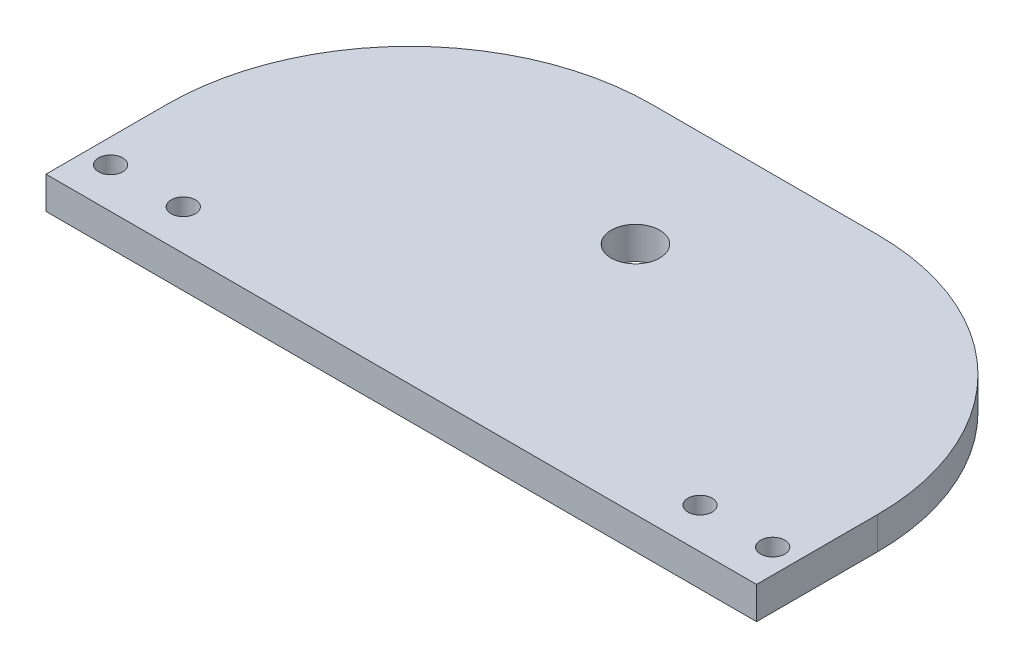
SolidWorks part; units mm, degrees
material "环氧树脂,未充填"
ref_plane "前视基准面" through (0, 0, 0) normal (0, 0, 1) x (1, 0, 0)
ref_plane "上视基准面" through (0, 0, 0) normal (0, 1, 0) x (1, 0, 0)
ref_plane "右视基准面" through (0, 0, 0) normal (1, 0, 0) x (0, 0, -1)
sketch "草图1" plane through (0, 0, 0) normal (0, 1, 0) x (1, 0, 0)
  line L1 (-44, 22.5) -> (44, 22.5)
  line L2 (-44, 22.5) -> (-44, -22.5)
  line L3 (-44, -22.5) -> (44, -22.5)
  line L4 (44, 22.5) -> (44, -22.5)
  line L5 (-44, 22.5) -> (44, -22.5) construction
  line L6 (-44, -22.5) -> (44, 22.5) construction
  point P0 (0, 0)
  dimension "D1" = 88
  dimension "D2" = 45
extrude "凸台-拉伸1" add sketch "草图1" along normal blind 4
sketch "草图2" plane through (0, 4, 0) normal (0, 1, 0) x (1, 0, 0)
  line L0 (-44, -22.5) -> (44, -22.5) construction
  circle A0 centre (0, 6.5) radius 3
  dimension "D1" = 6
  dimension "D2" = 29
extrude "切除-拉伸1" cut sketch "草图2" against normal blind 4
sketch "草图3" plane through (0, 4, 0) normal (0, 1, 0) x (1, 0, 0)
  line L0 (-36.5, -22.5) -> (-36.5, 22.5) construction
  line L1 (-44, -22.5) -> (44, -22.5) construction
  line L2 (44, 22.5) -> (-44, 22.5) construction
  line L3 (-44, 22.5) -> (-44, -22.5) construction
  line L4 (0, 22.5) -> (0, -22.5) construction
  circle A0 centre (-41, -17.5) radius 1.5
  circle A1 centre (-32, -17.5) radius 1.5
  circle A2 centre (32, -17.5) radius 1.5
  circle A3 centre (41, -17.5) radius 1.5
  dimension "D1" = 7.5
  dimension "D3" = 3
  dimension "D2" = 9
  dimension "D4" = 5
extrude "切除-拉伸2" cut sketch "草图3" against normal through all
fillet "圆角1" radius 30 2 edges at (44, 2, -22.5) (-44, 2, -22.5)
